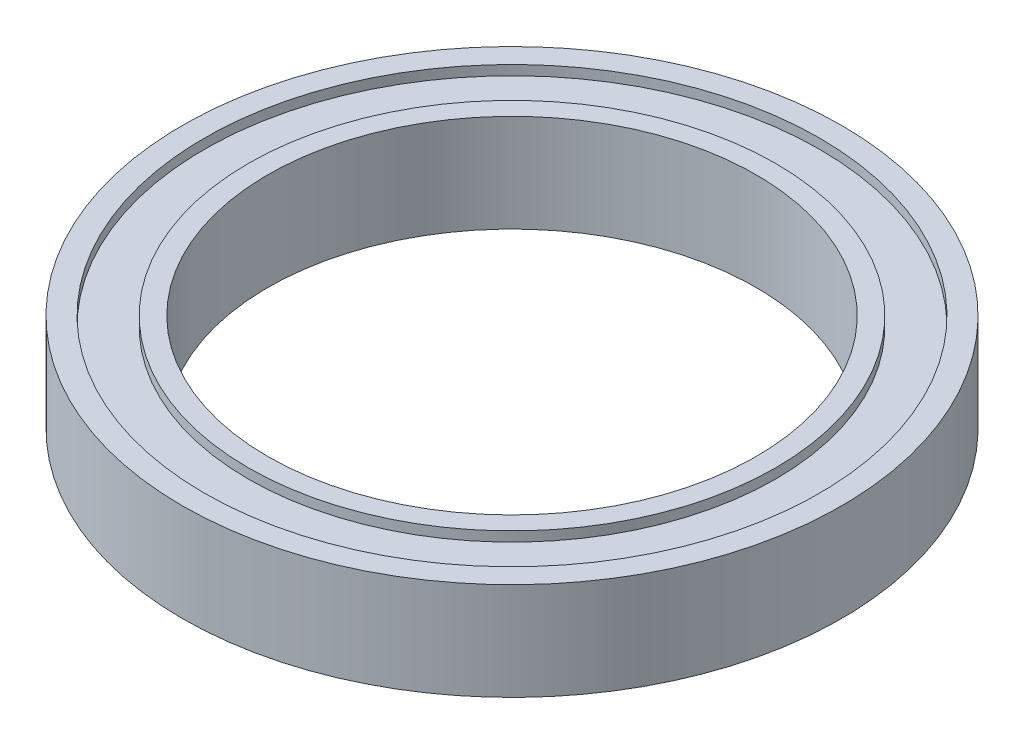
SolidWorks part; units mm, degrees
material "Stainless_Steel_Ruleman_6704"
ref_plane "Front Plane" through (0, 0, 0) normal (0, 0, 1) x (1, 0, 0)
ref_plane "Top Plane" through (0, 0, 0) normal (0, 1, 0) x (1, 0, 0)
ref_plane "Right Plane" through (0, 0, 0) normal (1, 0, 0) x (0, 0, -1)
sketch "Sketch1" plane through (0, 0, 0) normal (0, 1, 0) x (1, 0, 0)
  circle A0 centre (0, 0) radius 10
  circle A1 centre (0, 0) radius 13.5
  dimension "D1" = 20
  dimension "D2" = 27
extrude "Boss-Extrude1" add sketch "Sketch1" along normal blind 4
sketch "Sketch2" plane through (0, 4, 0) normal (0, 1, 0) x (1, 0, 0)
  circle A0 centre (0, 0) radius 12.6
  circle A1 centre (0, 0) radius 10.8
  circle A2 centre (0, 0) radius 13.5 construction
  circle A3 centre (0, 0) radius 10 construction
  dimension "D1" = 0.9
  dimension "D2" = 0.8
extrude "Cut-Extrude1" cut sketch "Sketch2" against normal blind 0.4
ref_plane "Plane1" through (0, 2, 0) normal (0, 1, 0) x (1, 0, 0)
mirror "Mirror1" about plane through (0, 2, 0) normal (0, 1, 0) of "Cut-Extrude1"
